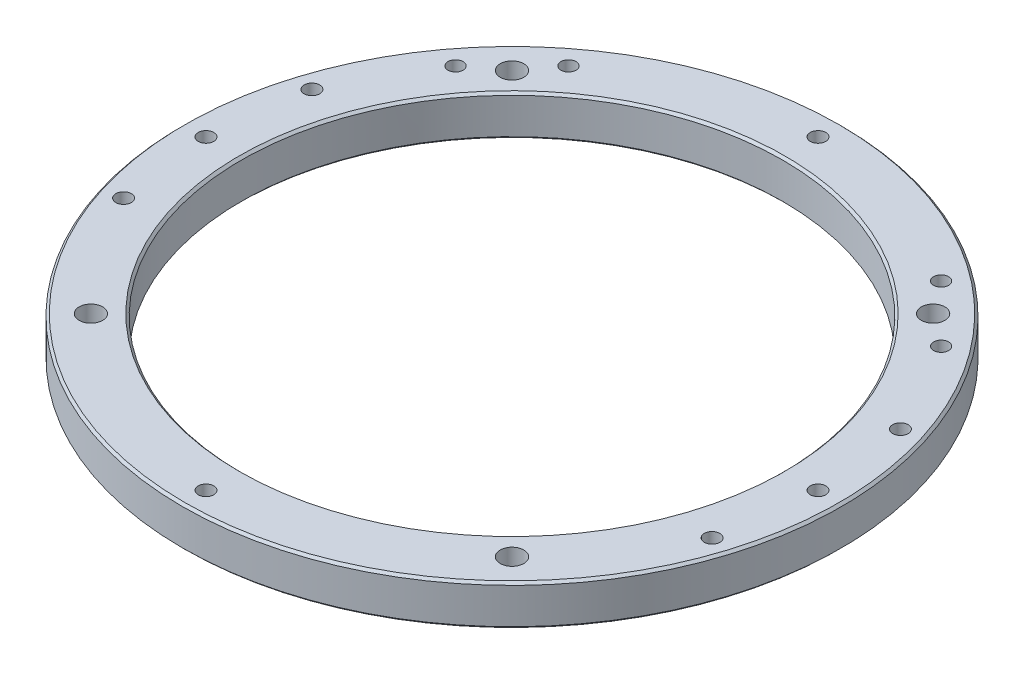
SolidWorks part; units mm, degrees
material "6061 合金"
ref_plane "正面" through (0, 0, 0) normal (0, 0, 1) x (1, 0, 0)
ref_plane "平面" through (0, 0, 0) normal (0, 1, 0) x (1, 0, 0)
ref_plane "右側面" through (0, 0, 0) normal (1, 0, 0) x (0, 0, -1)
sketch "ｽｹｯﾁ1" plane through (0, 0, 0) normal (0, 1, 0) x (1, 0, 0)
  circle A0 centre (0, 0) radius 57.5
  circle A1 centre (0, 0) radius 70
  dimension "D1" = 115
  dimension "D2" = 140
extrude "ﾎﾞｽ - 押し出し1" add sketch "ｽｹｯﾁ1" along normal blind 8.6
sketch "ｽｹｯﾁ2" plane through (0, 8.6, 0) normal (0, 1, 0) x (1, 0, 0)
  line L0 (0, 0) -> (-63.25, 0) construction
  line L1 (-44.7245, 44.7245) -> (0, 0) construction
  circle A0 centre (0, 0) radius 63.25 construction
  circle A1 centre (-44.7245, 44.7245) radius 2.5
  circle A2 centre (44.7245, 44.7245) radius 2.5
  circle A3 centre (44.7245, -44.7245) radius 2.5
  circle A4 centre (-44.7245, -44.7245) radius 2.5
  point P14 (0, 0)
  dimension "D1" = 126.5
  dimension "D2" = 5
  dimension "D4" = 45
  dimension "D3" = 4
extrude "ｶｯﾄ - 押し出し1" cut sketch "ｽｹｯﾁ2" against normal through all
chamfer "面取り1" distance 0.5 angle 45 4 edges at (0, 0, 70) (0, 8.6, 70) (0, 0, 57.5) (0, 8.6, 57.5)
sketch "ｽｹｯﾁ3" plane through (0, 8.6, 0) normal (0, 1, 0) x (1, 0, 0)
  line L0 (0, 0) -> (65, 0) construction
  line L1 (0, 0) -> (0, 58) construction
  circle A0 centre (0, 0) radius 65 construction
  circle A1 centre (65, 0) radius 1.65
  circle A2 centre (0, -65) radius 1.65
  circle A3 centre (-65, 0) radius 1.65
  circle A4 centre (0, 65) radius 1.65
  circle A5 centre (-62.5, 20) radius 1.65
  circle A6 centre (0, 0) radius 58 construction
  circle A7 centre (62.5, 20) radius 1.65
  circle A8 centre (62.5, -20) radius 1.65
  circle A9 centre (-62.5, -20) radius 1.65
  point P15 (0, 0)
  dimension "D1" = 130
  dimension "D3" = 3.3
  dimension "D2" = 3.3
  dimension "D4" = 125
  dimension "D5" = 40
extrude "ｶｯﾄ - 押し出し2" cut sketch "ｽｹｯﾁ3" against normal through all
sketch "ｽｹｯﾁ4" plane through (0, 8.6, 0) normal (0, 1, 0) x (1, 0, 0)
  line L0 (0, 0) -> (69.5, 0) construction
  line L1 (69.5, 0) -> (0, 0) construction
  line L2 (0, 0) -> (0, 65) construction
  line L3 (0, 65) -> (0, 0) construction
  line L4 (0, 0) -> (49.1439, 49.1439) construction
  line L5 (0, 0) -> (51.568, 39.5695) construction
  line L6 (0, 0) -> (39.5695, 51.568) construction
  circle A0 centre (0, 0) radius 69.5 construction
  circle A1 centre (51.568, 39.5695) radius 1.6
  circle A2 centre (0, 0) radius 65 construction
  circle A3 centre (39.5695, 51.568) radius 1.6
  circle A4 centre (-39.5695, 51.568) radius 1.6
  circle A5 centre (-51.568, 39.5695) radius 1.6
  dimension "D3" = 3.2
  dimension "D4" = 130
  dimension "D5" = 3.2
  dimension "D1" = 45
  dimension "D2" = 7.5
  dimension "D6" = 7.5
extrude "ｶｯﾄ - 押し出し3" cut sketch "ｽｹｯﾁ4" against normal through all
